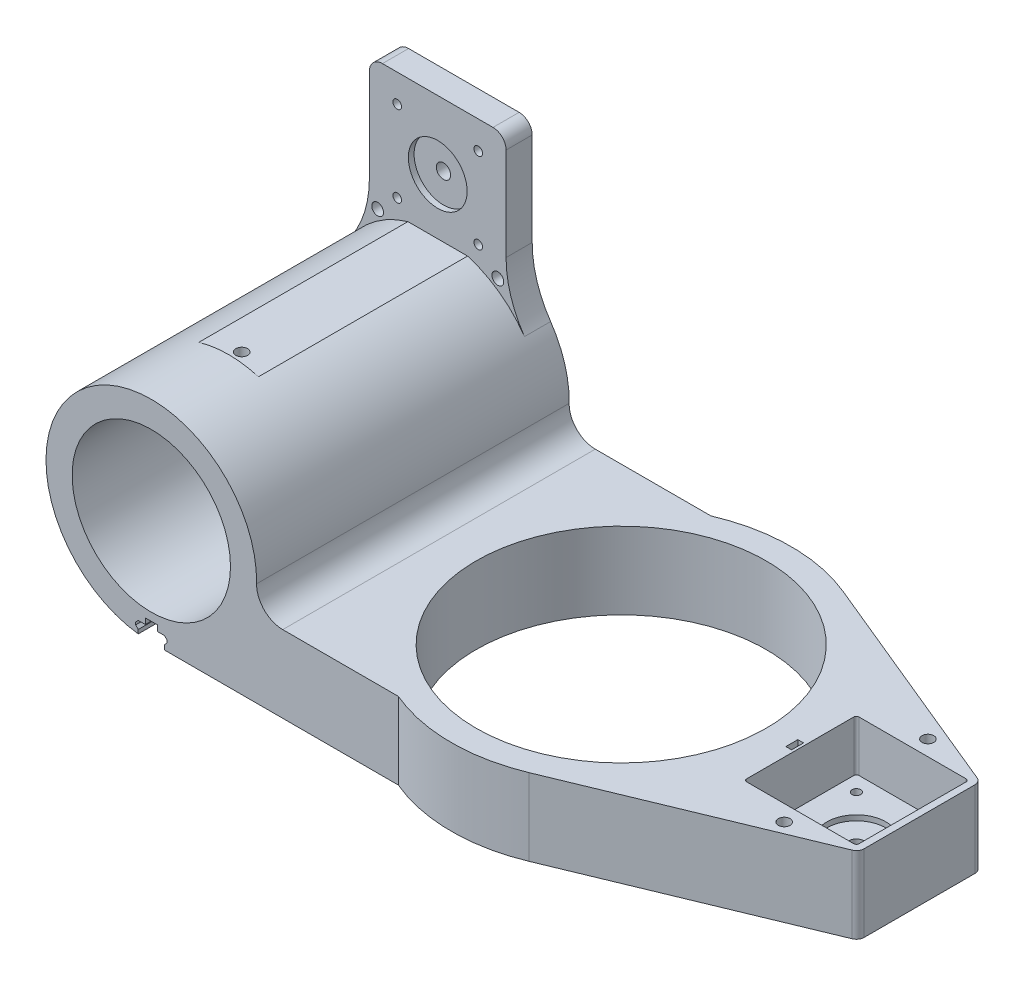
SolidWorks part; units mm, degrees
ref_plane "Front Plane" through (0, 0, 0) normal (0, 0, 1) x (1, 0, 0)
ref_plane "Top Plane" through (0, 0, 0) normal (0, 1, 0) x (1, 0, 0)
ref_plane "Right Plane" through (0, 0, 0) normal (1, 0, 0) x (0, 0, -1)
sketch "Sketch1" plane through (0, 0, 0) normal (0, 1, 0) x (1, 0, 0)
  line L0 (0, 0) -> (90, 0) construction
  line L1 (111.15, -24.15) -> (68.85, -24.15) construction
  line L2 (111.15, 21.15) -> (68.85, 21.15) construction
  line L3 (111.15, 21.15) -> (111.15, -21.15) construction
  line L4 (111.15, -21.15) -> (68.85, -21.15) construction
  line L5 (68.85, 21.15) -> (68.85, -21.15) construction
  line L6 (111.15, 21.15) -> (68.85, -21.15) construction
  line L7 (111.15, -21.15) -> (68.85, 21.15) construction
  line L8 (114.15, 21.15) -> (114.15, -21.15) construction
  line L9 (111.15, 24.15) -> (68.85, 24.15) construction
  line L10 (114.15, 24.15) -> (114.15, -24.15) construction
  line L11 (114.15, 24.15) -> (68.85, 24.15) construction
  line L12 (114.15, -24.15) -> (68.85, -24.15) construction
  line L13 (24.8266, -60.072) -> (112.2958, -23.9226)
  line L14 (112.2958, 23.9226) -> (24.8266, 60.072)
  line L15 (114.15, 21.15) -> (114.15, -21.15)
  circle A0 centre (0, 0) radius 55 construction
  circle A1 centre (0, 0) radius 55.5
  circle A2 centre (0, 0) radius 65 construction
  arc A3 (114.15, 21.15) -> (111.15, 24.15) centre (111.15, 21.15) ccw construction
  arc A4 (114.15, -21.15) -> (111.15, -24.15) centre (111.15, -21.15) cw construction
  arc A5 (114.15, -21.15) -> (112.2958, -23.9226) centre (111.15, -21.15) cw
  arc A6 (112.2958, 23.9226) -> (114.15, 21.15) centre (111.15, 21.15) cw
  arc A7 (24.8266, -60.072) -> (24.8266, 60.072) centre (0, 0) cw
  dimension "D1" = 110
  dimension "D3" = 130
  dimension "D7" = 3
  dimension "D4" = 90
  dimension "D5" = 42.3
  dimension "D2" = 0.5
  dimension "D6" = 3
extrude "Boss-Extrude1" add sketch "Sketch1" along normal blind 29.4
sketch "Sketch2" plane through (0, 29.4, 0) normal (0, 1, 0) x (1, 0, 0)
  line L0 (0, 0) -> (90, 0) construction
  line L2 (69.5, 21.5) -> (110.5, 21.5)
  line L3 (68.5, 20.5) -> (68.5, -20.5)
  line L4 (69.5, -21.5) -> (110.5, -21.5)
  line L5 (111.5, 20.5) -> (111.5, -20.5)
  line L6 (68.5, 21.5) -> (111.5, -21.5) construction
  line L7 (68.5, -21.5) -> (111.5, 21.5) construction
  arc A0 (69.5, 21.5) -> (68.5, 20.5) centre (69.5, 20.5) ccw
  arc A1 (110.5, 21.5) -> (111.5, 20.5) centre (110.5, 20.5) cw
  arc A2 (110.5, -21.5) -> (111.5, -20.5) centre (110.5, -20.5) ccw
  arc A3 (68.5, -20.5) -> (69.5, -21.5) centre (69.5, -20.5) ccw
  dimension "D3" = 1
  dimension "D1" = 90
  dimension "D2" = 43
extrude "Cut-Extrude1" cut sketch "Sketch2" against normal offset from surface (19.4 mm away) 10 up to face at (68.9267, 0, 0)
sketch "Sketch3" plane through (0, 10, 0) normal (0, 1, 0) x (1, 0, 0)
  line L0 (90, 0) -> (0, 0) construction
  line L1 (74.5, 15.5) -> (105.5, 15.5) construction
  line L2 (74.5, 15.5) -> (74.5, -15.5) construction
  line L3 (74.5, -15.5) -> (105.5, -15.5) construction
  line L4 (105.5, 15.5) -> (105.5, -15.5) construction
  line L5 (74.5, 15.5) -> (105.5, -15.5) construction
  line L6 (74.5, -15.5) -> (105.5, 15.5) construction
  circle A0 centre (74.5, -15.5) radius 1.65
  circle A1 centre (105.5, -15.5) radius 1.65
  circle A2 centre (105.5, 15.5) radius 1.65
  circle A3 centre (74.5, 15.5) radius 1.65
  circle A4 centre (90, 0) radius 2.8
  point P0 (90, 0)
  dimension "D2" = 3.3
  dimension "D4" = 5.6
  dimension "D1" = 90
  dimension "D3" = 31
extrude "Cut-Extrude2" cut sketch "Sketch3" against normal through all
sketch "Sketch4" plane through (0, 10, 0) normal (0, 1, 0) x (1, 0, 0)
  circle A0 centre (90, 0) radius 11.3
  dimension "D1" = 22.6
extrude "Cut-Extrude3" cut sketch "Sketch4" against normal blind 2
sketch "Sketch5" plane through (0, 0, 0) normal (0, -1, 0) x (1, 0, 0)
  circle A0 centre (74.5, 15.5) radius 3.3
  circle A1 centre (105.5, 15.5) radius 3.3
  circle A2 centre (74.5, -15.5) radius 3.3
  circle A3 centre (105.5, -15.5) radius 3.3
  dimension "D1" = 6.6
extrude "Cut-Extrude4" cut sketch "Sketch5" against normal blind 5
sketch "Sketch6" plane through (0, 0, 0) normal (0, 0, 1) x (1, 0, 0)
  line L0 (-65, 0) -> (24.8266, 0) construction
  circle A0 centre (-120, 40.3) radius 30.3
  circle A1 centre (-120, 40.3) radius 40.3
  dimension "D1" = 60.6
  dimension "D2" = 10
  dimension "D3" = 120
extrude "Boss-Extrude2" add sketch "Sketch6" along normal mid plane 119.6 separate body
sketch "Sketch7" plane through (0, 0, 59.8) normal (0, 0, 1) x (1, 0, 0)
  line L0 (-65, 29.4) -> (-65, 0)
  line L1 (-65, 0) -> (-120, 0)
  line L2 (-65, 29.4) -> (-81.2021, 29.4)
  circle A0 centre (-120, 40.3) radius 40.3 construction
  arc A1 (-120, 0) -> (-81.2021, 29.4) centre (-120, 40.3) ccw
extrude "Boss-Extrude3" add sketch "Sketch7" against normal up to surface (119.6 mm away) up to face at (-79.7, 40.3, -59.8)
sketch "Sketch8" plane through (0, 29.4, 0) normal (0, 1, 0) x (1, 0, 0)
  line L0 (-65, 59.8) -> (-65, -59.8) construction
  line L1 (-65, 59.8) -> (-65, -59.8)
  line L2 (-65, 59.8) -> (-25.4747, 59.8)
  line L3 (112.2958, 23.9226) -> (24.8266, 60.072)
  line L4 (24.8266, -60.072) -> (112.2958, -23.9226)
  line L5 (114.15, -21.15) -> (114.15, 21.15)
  line L9 (-65, -59.8) -> (-25.4747, -59.8)
  arc A3 (114.15, 21.15) -> (112.2958, 23.9226) centre (111.15, 21.15) ccw
  arc A4 (24.8266, 60.072) -> (24.8266, -60.072) centre (0, 0) ccw
  arc A5 (112.2958, -23.9226) -> (114.15, -21.15) centre (111.15, -21.15) ccw
  arc A7 (-25.4747, 59.8) -> (-25.4747, -59.8) centre (0, 0) ccw
  arc M17 (24.8266, 60.072) -> (24.8266, -60.072) centre (0, 0) ccw
  dimension "D1" = 0
extrude "Boss-Extrude4" add sketch "Sketch8" against normal up to surface (29.4 mm away) contours L1 L9 M17 | L2 L1 M17 up to face at (105.5, 0, 12.2)
fillet "Fillet1" radius 10 1 edges at (-81.2021, 29.4, 0)
sketch "Sketch9" plane through (0, 29.4, 0) normal (0, 1, 0) x (1, 0, 0)
  line L0 (68.5, 20.5) -> (68.5, -20.5) construction
  line L1 (65.3, 2.3) -> (67.5, 2.3)
  line L2 (65.3, 2.3) -> (65.3, -2.3)
  line L3 (65.3, -2.3) -> (67.5, -2.3)
  line L4 (67.5, 2.3) -> (67.5, -2.3)
  line L5 (65.3, 0) -> (0, 0) construction
  dimension "D1" = 4.6
  dimension "D2" = 2.2
  dimension "D3" = 1
extrude "Cut-Extrude5" cut sketch "Sketch9" against normal blind 11.5
sketch "Sketch10" plane through (0, 29.4, 0) normal (0, 1, 0) x (1, 0, 0)
  line L0 (90, -27.6126) -> (90, 27.3874) construction
  circle A0 centre (90, -27.6126) radius 2.25
  circle A1 centre (90, 27.3874) radius 2.25
  point P5 (90, -0.1126)
  dimension "D2" = 4.5
  dimension "D1" = 55
extrude "Cut-Extrude6" cut sketch "Sketch10" against normal blind 8
sketch "Sketch12" plane through (0, 0, -59.8) normal (0, 0, -1) x (-1, 0, 0)
  line L0 (120, 40.3) -> (120, 100.3) construction
  line L2 (93.85, 70.9638) -> (146.15, 70.9638)
  line L3 (93.85, 70.9638) -> (93.85, 126.45)
  line L4 (93.85, 126.45) -> (146.15, 126.45)
  line L5 (146.15, 70.9638) -> (146.15, 126.45)
  circle A0 centre (120, 100.3) radius 2.75
  arc A1 (120, 0) -> (79.7065, 39.5789) centre (120, 40.3) ccw construction
  point P11 (0, 0)
  dimension "D2" = 5.5
  dimension "D1" = 60
  dimension "D3" = 26.15
  dimension "D4" = 52.3
extrude "Boss-Extrude5" add sketch "Sketch12" against normal blind 10
sketch "Sketch13" plane through (0, 0, -59.8) normal (0, 0, -1) x (-1, 0, 0)
  line L1 (135.5, 84.8) -> (104.5, 84.8) construction
  line L2 (135.5, 84.8) -> (135.5, 115.8) construction
  line L3 (135.5, 115.8) -> (104.5, 115.8) construction
  line L4 (104.5, 84.8) -> (104.5, 115.8) construction
  line L5 (135.5, 84.8) -> (104.5, 115.8) construction
  line L6 (135.5, 115.8) -> (104.5, 84.8) construction
  circle A0 centre (104.5, 115.8) radius 1.65
  circle A1 centre (104.5, 84.8) radius 1.65
  circle A2 centre (135.5, 84.8) radius 1.65
  circle A3 centre (135.5, 115.8) radius 1.65
  point P0 (120, 100.3)
  dimension "D2" = 3.3
  dimension "D1" = 31
extrude "Cut-Extrude7" cut sketch "Sketch13" against normal through all
sketch "Sketch14" plane through (0, 0, -59.8) normal (0, 0, -1) x (-1, 0, 0)
  circle A0 centre (104.5, 115.8) radius 3.3
  circle A1 centre (104.5, 84.8) radius 3.3
  circle A2 centre (135.5, 84.8) radius 3.3
  circle A3 centre (135.5, 115.8) radius 3.3
  dimension "D1" = 6.6
extrude "Cut-Extrude8" cut sketch "Sketch14" against normal blind 6
sketch "Sketch15" plane through (0, 0, -49.8) normal (0, 0, 1) x (1, 0, 0)
  line L1 (-141.35, 121.65) -> (-98.65, 121.65)
  line L2 (-141.35, 121.65) -> (-141.35, 78.95)
  line L3 (-141.35, 78.95) -> (-98.65, 78.95)
  line L4 (-98.65, 121.65) -> (-98.65, 78.95)
  line L5 (-141.35, 121.65) -> (-98.65, 78.95) construction
  line L6 (-141.35, 78.95) -> (-98.65, 121.65) construction
  point P0 (-120, 100.3)
  dimension "D1" = 42.7
extrude "Cut-Extrude9" cut sketch "Sketch15" along normal blind 80
fillet "Fillet2" radius 40 2 edges at (-93.85, 70.9638, -54.8) (-146.15, 70.9638, -54.8)
fillet "Fillet3" radius 5 2 edges at (-93.85, 126.45, -54.8) (-146.15, 126.45, -54.8)
sketch "Sketch16" plane through (0, 0, -49.8) normal (0, 0, 1) x (1, 0, 0)
  line L0 (-120, 100.3) -> (-120, 77.3) construction
  line L1 (-97, 77.3) -> (-143, 77.3) construction
  circle A0 centre (-143, 77.3) radius 2.25
  circle A1 centre (-97, 77.3) radius 2.25
  point P6 (-120, 77.3)
  point P8 (-120, 78.9873)
  point P9 (-141.8473, 80.0859)
  dimension "D1" = 4.5
  dimension "D2" = 46
  dimension "D3" = 23
extrude "Cut-Extrude10" cut sketch "Sketch16" against normal blind 4
sketch "Sketch17" plane through (0, 78.95, 0) normal (0, 1, 0) x (1, 0, 0)
  line L0 (-120, 49.8) -> (-120, -25.2) construction
  line L1 (-131.4135, 49.8) -> (-108.5865, 49.8) construction
  circle A0 centre (-120, -25.2) radius 2.25
  dimension "D1" = 4.5
  dimension "D2" = 75
extrude "Cut-Extrude11" cut sketch "Sketch17" against normal blind 7
sketch "Sketch18" plane through (0, 0, 59.8) normal (0, 0, 1) x (1, 0, 0)
  line L0 (-120, 40.3) -> (-120, 7) construction
  line L14 (-122.3, 7) -> (-117.7, 7)
  line L15 (-122.3, 7) -> (-122.3, 4.8)
  line L21 (-122.3, 4.8) -> (-117.7, 4.8) construction
  line L22 (-117.7, 7) -> (-117.7, 4.8)
  line L23 (-122.3, 7) -> (-117.7, 4.8) construction
  line L24 (-122.3, 4.8) -> (-117.7, 7) construction
  line L25 (-120, 0) -> (-25.4747, 0) construction
  line L26 (-125, 4.8) -> (-115, 4.8) construction
  line L27 (-125, 1.8) -> (-125, 0)
  line L28 (-125, 0) -> (-115, 0)
  line L29 (-115, 1.8) -> (-115, 0)
  line L30 (-125, 4.8) -> (-122.3, 4.8)
  line L31 (-117.7, 4.8) -> (-115, 4.8)
  line L32 (-125, 4.8) -> (-126, 3.8)
  line L33 (-126, 3.8) -> (-126, 2.8)
  line L34 (-126, 2.8) -> (-125, 1.8)
  line L35 (-115, 4.8) -> (-114, 3.8)
  line L36 (-114, 3.8) -> (-114, 2.8)
  line L37 (-114, 2.8) -> (-115, 1.8)
  circle A3 centre (-120, 40.3) radius 30.3 construction
  point P0 (-120, 5.9)
  point P7 (-120, 10)
  point P15 (-120, 4.8)
  point P16 (-120, 4.8)
  dimension "D1" = 2.2
  dimension "D2" = 4.6
  dimension "D3" = 3
  dimension "D4" = 10
  dimension "D5" = 45
  dimension "D6" = 1
  dimension "D7" = 1
  dimension "D8" = 1
extrude "Cut-Extrude14" cut sketch "Sketch18" against normal blind 20
sketch "Sketch20" plane through (0, 0, -49.8) normal (0, 0, 1) x (1, 0, 0)
  circle A0 centre (-120, 100.3) radius 11.25
  dimension "D1" = 22.5
extrude "Cut-Extrude15" cut sketch "Sketch20" against normal blind 2.2
